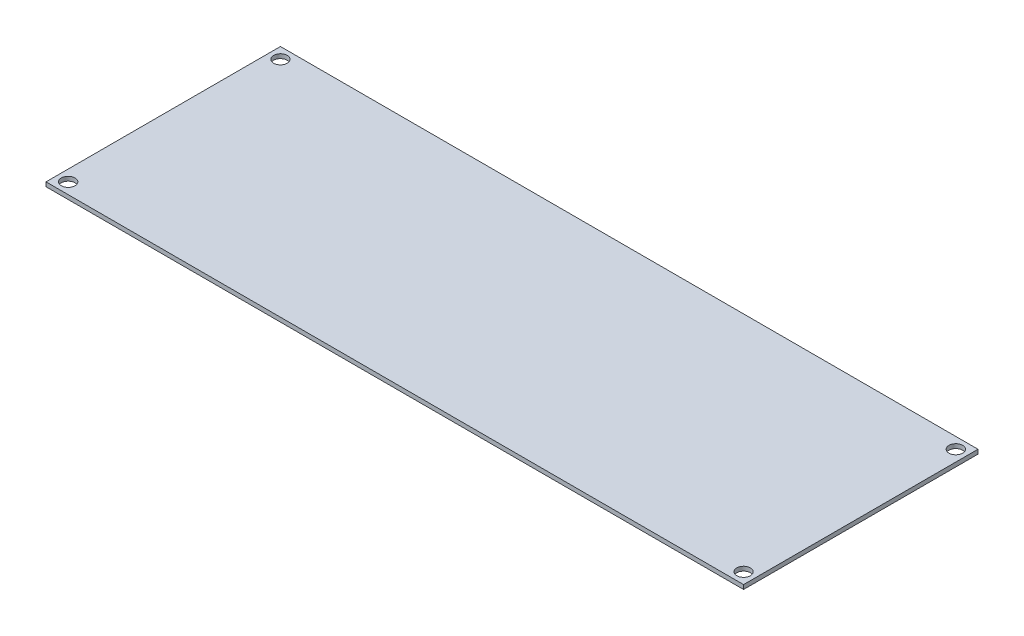
SolidWorks part; units mm, degrees
ref_plane "Front Plane" through (0, 0, 0) normal (0, 0, 1) x (1, 0, 0)
ref_plane "Top Plane" through (0, 0, 0) normal (0, 1, 0) x (1, 0, 0)
ref_plane "Right Plane" through (0, 0, 0) normal (1, 0, 0) x (0, 0, -1)
sketch "Sketch1" plane through (0, 0, 0) normal (0, 1, 0) x (1, 0, 0)
  line L1 (-81.83, -27.5) -> (81.83, -27.5)
  line L2 (-81.83, -27.5) -> (-81.83, 27.5)
  line L3 (-81.83, 27.5) -> (81.83, 27.5)
  line L4 (81.83, -27.5) -> (81.83, 27.5)
  line L5 (-81.83, -27.5) -> (81.83, 27.5) construction
  line L6 (-81.83, 27.5) -> (81.83, -27.5) construction
  circle A0 centre (79.23, 24.9) radius 1.6
  circle A1 centre (79.23, -24.9) radius 1.6
  circle A2 centre (-79.23, -24.9) radius 1.6
  circle A3 centre (-79.23, 24.9) radius 1.6
  point P0 (0, 0)
  dimension "D5" = 3.2
  dimension "D1" = 163.66
  dimension "D2" = 55
  dimension "D3" = 2.6
  dimension "D4" = 2.6
  dimension "D6" = 158.46
  dimension "D7" = 49.8
extrude "Boss-Extrude1" add sketch "Sketch1" along normal blind 1
